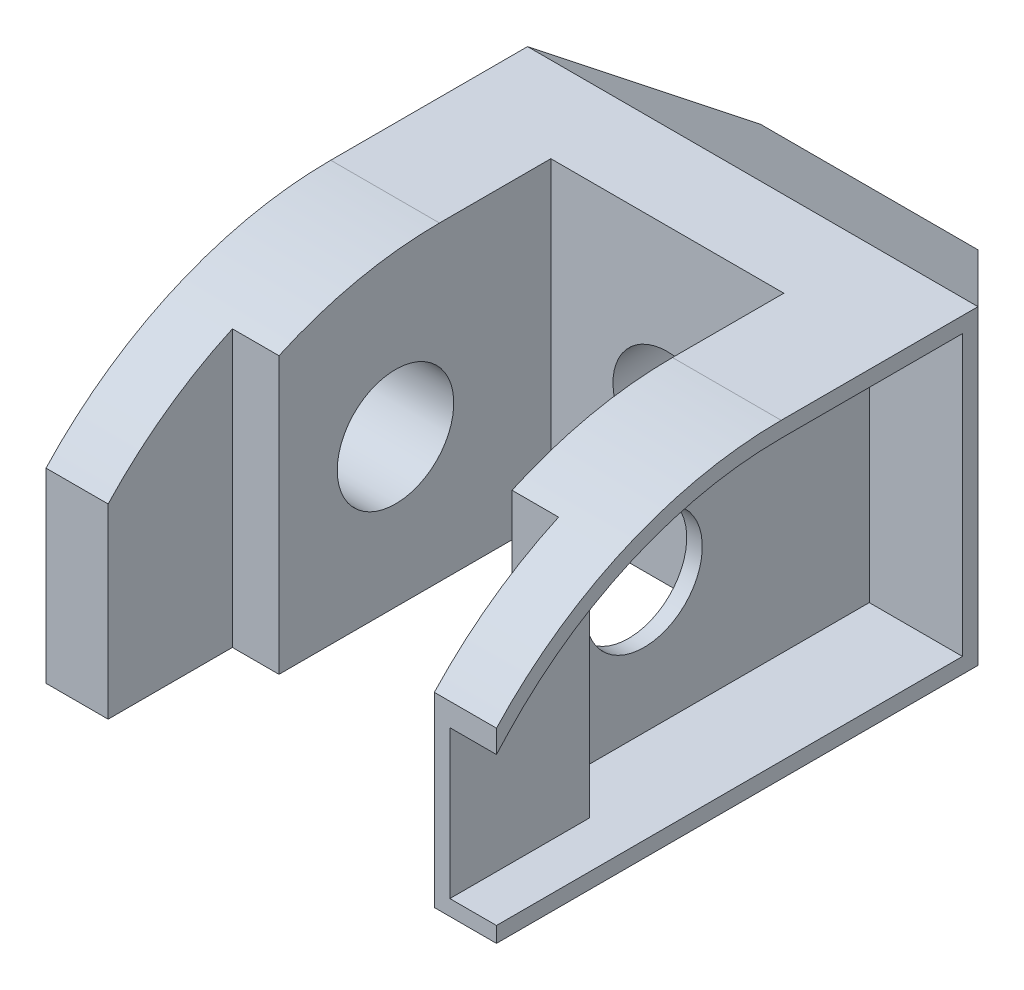
SolidWorks part; units mm, degrees
material "1060 Alloy"
ref_plane "Front Plane" through (0, 0, 0) normal (0, 0, 1) x (1, 0, 0)
ref_plane "Top Plane" through (0, 0, 0) normal (0, 1, 0) x (1, 0, 0)
ref_plane "Right Plane" through (0, 0, 0) normal (1, 0, 0) x (0, 0, -1)
sketch "Sketch1" plane through (0, 0, 0) normal (1, 0, 0) x (0, 0, -1)
  line L0 (0, 0) -> (0, 22637.3905) construction
  line L1 (1.3894, 0) -> (-22636.0011, 0) construction
  line L2 (-31, 5) -> (-31, -19)
  line L3 (-31, -19) -> (31, -19)
  line L4 (31, -19) -> (46, -10.3397)
  line L5 (46, -10.3397) -> (46, 12.3397)
  line L6 (46, 12.3397) -> (31, 21)
  line L7 (31, 21) -> (5.6606, 21)
  arc A0 (5.6606, 21) -> (-31, 5) centre (5.6606, -29) ccw
  circle A1 centre (0, 0) radius 7.5
  dimension "D7" = 15
  dimension "D11" = 50
  dimension "D2" = 40
  dimension "D3" = 30
  dimension "D4" = 30
  dimension "D5" = 15
  dimension "D6" = 15
  dimension "D8" = 31
  dimension "D9" = 19
  dimension "D10" = 24
  dimension "D12" = 62
extrude "Boss-Extrude1" add sketch "Sketch1" along normal mid plane 58
sketch "Sketch2" plane through (0, 21, 0) normal (0, 1, 0) x (1, 0, 0)
  line L0 (-29, 31) -> (-29, 56.131) construction
  line L1 (29, 31) -> (29, 54.4301) construction
  line L2 (-29, 31) -> (-14, 46)
  line L3 (29, 46) -> (-29, 46) construction
  line L4 (-14, 46) -> (-29, 46)
  line L5 (-29, 46) -> (-29, 31)
  line L6 (29, 31) -> (29, 46)
  line L7 (29, 46) -> (14, 46)
  line L8 (14, 46) -> (29, 31)
  dimension "D1" = 45
  dimension "D2" = 45
extrude "Cut-Extrude1" cut sketch "Sketch2" against normal through all
sketch "Sketch3" plane through (0, 0, -46) normal (0, 0, -1) x (-1, 0, 0)
  circle A0 centre (0, 0) radius 7
  dimension "D1" = 14
extrude "Cut-Extrude2" cut sketch "Sketch3" against normal through all
sketch "Sketch4" plane through (0, 21, 0) normal (0, 1, 0) x (1, 0, 0)
  line L0 (0, 0) -> (50000, 0) construction
  line L1 (0, 0) -> (0, 50000) construction
  line L2 (-21, -31) -> (21, -31)
  line L3 (-4.899, -31) -> (-29, -31) construction
  line L4 (-21, -31) -> (-21, -15)
  line L5 (-21, -15) -> (-15, -15)
  line L6 (-15, -15) -> (-15, 20)
  line L7 (-15, 20) -> (15, 20)
  line L8 (15, 20) -> (15, -15)
  line L9 (15, -15) -> (21, -15)
  line L10 (21, -15) -> (21, -31)
  line L11 (29, -31) -> (4.899, -31) construction
  line L12 (29, 31) -> (-29, 31) construction
  line L14 (29, -31) -> (29, 5.6606) construction
  line L15 (-29, 5.6606) -> (-29, -31) construction
  dimension "D1" = 11
  dimension "D2" = 16
  dimension "D3" = 8
  dimension "D4" = 6
  dimension "D5" = 8
extrude "Cut-Extrude3" cut sketch "Sketch4" against normal through all
sketch "Sketch6" plane through (29, 0, 0) normal (1, 0, 0) x (0, 0, -1)
  line L10 (-31, 5) -> (-31, -19) construction
  line L11 (-31, 2.0588) -> (-31, -17)
  line L12 (-29.5336, 3.64) -> (-31, 2.0588)
  line L13 (-31, -17) -> (29, -17)
  line L14 (29, -17) -> (29, 19)
  line L15 (29, 19) -> (5.6606, 19)
  line L16 (-31, -17) -> (29, -17)
  line L17 (29, -17) -> (29, 19)
  line L18 (29, 19) -> (5.6606, 19)
  arc A6 (5.6606, 19) -> (-29.5336, 3.64) centre (5.6606, -29) ccw
  arc A7 (5.6606, 19) -> (-29.5336, 3.64) centre (5.6606, -29) ccw
  point P0 (0, 0)
  dimension "D1" = 2
extrude "Cut-Extrude4" cut sketch "Sketch6" against normal offset from surface (6 mm away) 2 up to face at (21, -3.9179, 23.1436)
sketch "Sketch7" plane through (23, 0, 0) normal (1, 0, 0) x (0, 0, -1)
  line L4 (-13, -19) -> (-13, 16.5317)
  line L5 (-29.5336, 3.64) -> (-31, 2.0588)
  line L6 (-31, 2.0588) -> (-31, -17)
  line L7 (-31, -17) -> (29, -17)
  line L8 (29, -17) -> (29, 19)
  line L9 (29, 19) -> (5.6606, 19)
  line L12 (-13, -17) -> (29, -17)
  line L13 (29, -17) -> (29, 19)
  line L14 (29, 19) -> (5.6606, 19)
  line L15 (-13, -17) -> (-13, 15.2242)
  arc A1 (5.6606, 19) -> (-29.5336, 3.64) centre (5.6606, -29) ccw
  arc A2 (5.6606, 19) -> (-13, 15.2242) centre (5.6606, -29) ccw
  dimension "D1" = 0
  dimension "D2" = 2
extrude "Cut-Extrude5" cut sketch "Sketch7" against normal offset from surface (6 mm away) 2 up to face at (15, 0, -7.5)
equation "\"A\"= 58"
equation "\"B\"= 40"
equation "\"C\"= 62"
equation "\"D2@Sketch1\"=\"B\""
equation "\"D1@Boss-Extrude1\"=\"A\""
equation "\"D12@Sketch1\"=\"C\""
